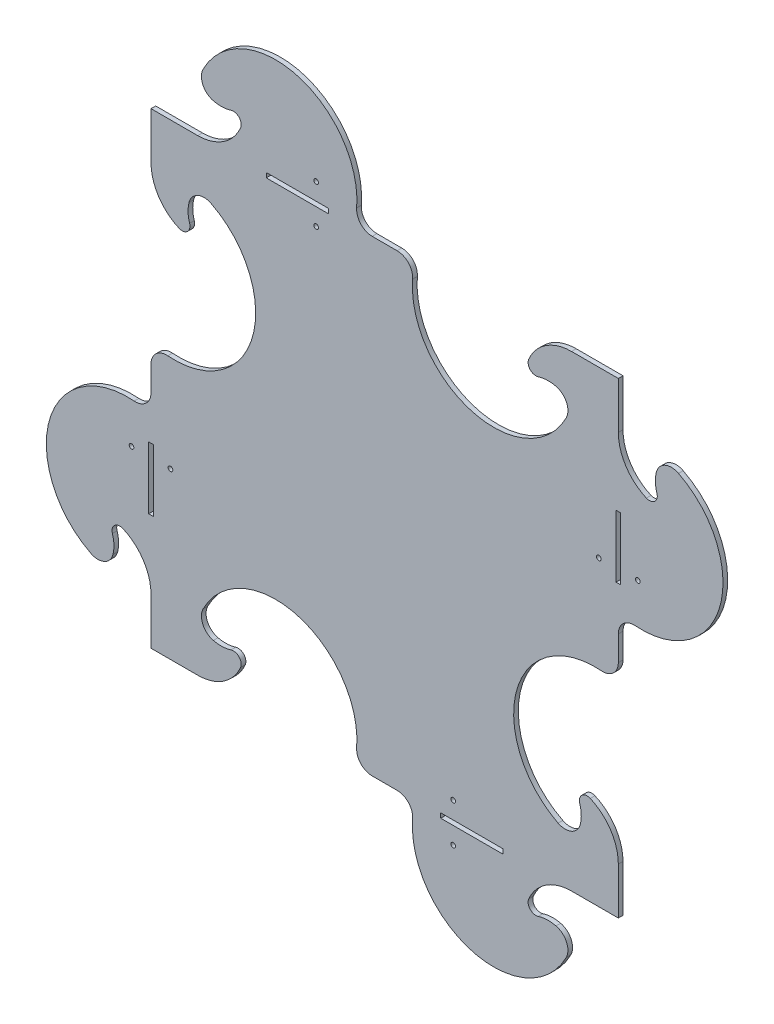
SolidWorks part; units mm, degrees
ref_plane "Plano frontal" through (0, 0, 0) normal (0, 0, 1) x (1, 0, 0)
ref_plane "Plano superior" through (0, 0, 0) normal (0, 1, 0) x (1, 0, 0)
ref_plane "Plano direito" through (0, 0, 0) normal (1, 0, 0) x (0, 0, -1)
sketch "Esboço1" plane through (0, 0, 0) normal (0, 0, 1) x (1, 0, 0)
  line L0 (-241.2037, -59.6514) -> (-241.2037, -29.6514)
  line L1 (-241.2037, 240.3486) -> (58.7963, 240.3486) construction
  line L2 (-241.2037, 240.3486) -> (-241.2037, -59.6514) construction
  line L3 (-241.2037, -59.6514) -> (58.7963, -59.6514) construction
  line L4 (58.7963, 240.3486) -> (58.7963, -59.6514) construction
  line L5 (-241.2037, -29.6514) -> (-241.2037, 0.3486) construction
  line L6 (-241.2037, -29.6514) -> (-241.2037, 70.3486) construction
  line L7 (-241.2037, -29.6514) -> (-271.2037, -29.6514) construction
  line L8 (-241.2037, -29.6514) -> (-241.2037, 0.3486) construction
  line L9 (-241.2037, 240.3486) -> (-241.2037, 210.3486)
  line L10 (-241.2037, 210.3486) -> (-241.2037, 110.3486) construction
  line L11 (-241.2037, 210.3486) -> (-241.2037, 110.3486) construction
  line L12 (-241.2037, 82.3489) -> (-241.2037, 98.3484)
  line L13 (-241.2037, 210.3486) -> (-211.2037, 210.3486) construction
  line L14 (-241.2037, 240.3486) -> (-211.2037, 240.3486)
  line L15 (-211.2037, 240.3486) -> (-111.2037, 240.3486) construction
  line L16 (-211.2037, 240.3486) -> (-211.2037, 270.3486) construction
  line L17 (-211.2037, 240.3486) -> (-181.2037, 240.3486) construction
  line L18 (-99.2034, 240.3486) -> (-83.2039, 240.3486)
  line L19 (58.7963, 240.3486) -> (28.7963, 240.3486)
  line L20 (28.7963, 240.3486) -> (-71.2037, 240.3486) construction
  line L21 (28.7963, 240.3486) -> (-1.2037, 240.3486) construction
  line L22 (28.7963, 240.3486) -> (28.7963, 210.3486) construction
  line L23 (58.7963, 240.3486) -> (58.7963, 210.3486)
  line L24 (-241.2037, -59.6514) -> (-211.2037, -59.6514)
  line L25 (58.7963, -59.6514) -> (28.7963, -59.6514)
  line L26 (58.7963, -59.6514) -> (58.7963, -29.6514)
  line L27 (-211.2037, -59.6514) -> (-181.2037, -59.6514) construction
  line L28 (28.7963, -59.6514) -> (-1.2037, -59.6514) construction
  line L29 (-211.2037, -59.6514) -> (-111.2037, -59.6514) construction
  line L30 (-211.2037, -59.6514) -> (-211.2037, -29.6514) construction
  line L31 (-211.2037, -59.6514) -> (-181.2037, -59.6514) construction
  line L32 (28.7963, -59.6514) -> (-71.2037, -59.6514) construction
  line L33 (28.7963, -59.6514) -> (28.7963, -89.6514) construction
  line L34 (-83.2039, -59.6514) -> (-99.2034, -59.6514)
  line L35 (58.7963, -29.6514) -> (58.7963, 0.3486) construction
  line L36 (58.7963, -29.6514) -> (58.7963, 70.3486) construction
  line L37 (58.7963, -29.6514) -> (58.7963, 70.3486) construction
  line L38 (58.7963, 210.3486) -> (58.7963, 180.3486) construction
  line L39 (58.7963, 210.3486) -> (58.7963, 110.3486) construction
  line L40 (58.7963, 210.3486) -> (88.7963, 210.3486) construction
  line L41 (58.7963, 98.3484) -> (58.7963, 82.3489)
  line L42 (58.7963, -29.6514) -> (28.7963, -29.6514) construction
  line L43 (28.7963, 240.3486) -> (-71.2037, 240.3486) construction
  line L44 (-241.2037, 210.3486) -> (-241.2037, 180.3486) construction
  line L45 (58.7963, 210.3486) -> (58.7963, 180.3486) construction
  arc A0 (-241.2037, -29.6514) -> (-259.2171, -2.15) centre (-271.2037, -29.6514) ccw
  arc A1 (-265.9813, -8.2439) -> (-265.5831, -19.6303) centre (-286.2037, -14.6514) cw
  arc A2 (-279.8296, -26.2004) -> (-252.0075, 72.3813) centre (-256.2037, 20.3486) cw
  arc A3 (-241.2037, 210.3486) -> (-223.1903, 182.8473) centre (-211.2037, 210.3486) ccw
  arc A4 (-216.4261, 188.9412) -> (-216.8243, 200.3276) centre (-196.2037, 195.3486) cw
  arc A5 (-202.5777, 206.8977) -> (-230.3998, 108.316) centre (-226.2037, 160.3486) cw
  arc A6 (-230.3998, 108.316) -> (-241.2037, 98.3484) centre (-231.2037, 98.3484) ccw
  arc A7 (-202.5777, 206.8977) -> (-216.8243, 200.3276) centre (-207.1037, 197.9805) ccw
  arc A8 (-241.2037, 82.3489) -> (-252.0075, 72.3813) centre (-251.2037, 82.3489) cw
  arc A9 (-265.5831, -19.6303) -> (-279.8296, -26.2004) centre (-275.3037, -17.2832) cw
  arc A10 (-223.1903, 182.8473) -> (-216.4261, 188.9412) centre (-221.1925, 187.4309) ccw
  arc A11 (-259.2171, -2.15) -> (-265.9813, -8.2439) centre (-261.2149, -6.7336) ccw
  arc A12 (-211.2037, 240.3486) -> (-183.7024, 258.3621) centre (-211.2037, 270.3486) ccw
  arc A13 (-189.7962, 265.1263) -> (-201.1827, 264.728) centre (-196.2037, 285.3486) cw
  arc A14 (-207.7527, 278.9746) -> (-109.1711, 251.1525) centre (-161.2037, 255.3486) cw
  arc A15 (-99.2034, 240.3486) -> (-109.1711, 251.1525) centre (-99.2034, 250.3486) cw
  arc A16 (-207.7527, 278.9746) -> (-201.1827, 264.728) centre (-198.8356, 274.4487) ccw
  arc A17 (28.7963, 240.3486) -> (1.295, 222.3352) centre (28.7963, 210.3486) ccw
  arc A18 (7.3888, 215.571) -> (18.7753, 215.9693) centre (13.7963, 195.3486) cw
  arc A19 (25.3454, 201.7227) -> (-73.2363, 229.5448) centre (-21.2037, 225.3486) cw
  arc A20 (-189.7962, 265.1263) -> (-183.7024, 258.3621) centre (-188.2859, 260.3598) cw
  arc A21 (18.7753, 215.9693) -> (25.3454, 201.7227) centre (16.4282, 206.2486) cw
  arc A22 (-83.2039, 240.3486) -> (-73.2363, 229.5448) centre (-83.2039, 230.3486) cw
  arc A23 (1.295, 222.3352) -> (7.3888, 215.571) centre (5.8786, 220.3375) ccw
  arc A24 (-211.2037, -59.6514) -> (-183.7024, -41.6379) centre (-211.2037, -29.6514) ccw
  arc A25 (-189.7962, -34.8737) -> (-201.1827, -35.272) centre (-196.2037, -14.6514) cw
  arc A26 (-207.7527, -21.0254) -> (-109.1711, -48.8475) centre (-161.2037, -44.6514) cw
  arc A27 (28.7963, -59.6514) -> (1.295, -77.6648) centre (28.7963, -89.6514) ccw
  arc A28 (7.3888, -84.429) -> (18.7753, -84.0307) centre (13.7963, -104.6514) cw
  arc A29 (25.3454, -98.2773) -> (-73.2363, -70.4552) centre (-21.2037, -74.6514) cw
  arc A30 (-99.2034, -59.6514) -> (-109.1711, -48.8475) centre (-99.2034, -49.6514) cw
  arc A31 (-201.1827, -35.272) -> (-207.7527, -21.0254) centre (-198.8356, -25.5513) cw
  arc A32 (18.7753, -84.0307) -> (25.3454, -98.2773) centre (16.4282, -93.7514) cw
  arc A33 (-83.2039, -59.6514) -> (-73.2363, -70.4552) centre (-83.2039, -69.6514) cw
  arc A34 (-189.7962, -34.8737) -> (-183.7024, -41.6379) centre (-188.2859, -39.6402) cw
  arc A35 (1.295, -77.6648) -> (7.3888, -84.429) centre (5.8786, -79.6625) ccw
  arc A36 (58.7963, -29.6514) -> (40.7829, -2.15) centre (28.7963, -29.6514) ccw
  arc A37 (34.0187, -8.2439) -> (34.4169, -19.6303) centre (13.7963, -14.6514) cw
  arc A38 (20.1704, -26.2004) -> (47.9925, 72.3813) centre (43.7963, 20.3486) cw
  arc A39 (58.7963, 210.3486) -> (76.8097, 182.8473) centre (88.7963, 210.3486) ccw
  arc A40 (83.5739, 188.9412) -> (83.1757, 200.3276) centre (103.7963, 195.3486) cw
  arc A41 (97.4223, 206.8977) -> (69.6002, 108.316) centre (73.7963, 160.3486) cw
  arc A42 (69.6002, 108.316) -> (58.7963, 98.3484) centre (68.7963, 98.3484) ccw
  arc A43 (97.4223, 206.8977) -> (83.1757, 200.3276) centre (92.8963, 197.9805) ccw
  arc A44 (40.7829, -2.15) -> (34.0187, -8.2439) centre (38.7851, -6.7336) ccw
  arc A45 (58.7963, 82.3489) -> (47.9925, 72.3813) centre (48.7963, 82.3489) cw
  arc A46 (34.4169, -19.6303) -> (20.1704, -26.2004) centre (24.6963, -17.2832) cw
  arc A47 (83.5739, 188.9412) -> (76.8097, 182.8473) centre (78.8075, 187.4309) cw
  dimension "D10" = 30
  dimension "D11" = 10
  dimension "D12" = 10
  dimension "D13" = 5
  dimension "D14" = 5
  dimension "D19" = 10
  dimension "D20" = 5
  dimension "D25" = 10
  dimension "D26" = 10
  dimension "D27" = 10
  dimension "D38" = 30
  dimension "D39" = 5
  dimension "D40" = 5
  dimension "D41" = 10
  dimension "D42" = 9.9676
  dimension "D48" = 5
  dimension "D49" = 5
  dimension "D50" = 10
  dimension "D24" = 30
  dimension "D51" = 10
  dimension "D52" = 5
  dimension "D1" = 300
  dimension "D2" = 300
  dimension "D3" = 30
  dimension "D4" = 30
  dimension "D5" = 100
  dimension "D6" = 30
  dimension "D7" = 30
  dimension "D8" = 100
  dimension "D9" = 30
  dimension "D15" = 30
  dimension "D16" = 100
  dimension "D17" = 30
  dimension "D18" = 30
  dimension "D21" = 30
  dimension "D22" = 100
  dimension "D23" = 30
  dimension "D28" = 30
  dimension "D29" = 30
  dimension "D30" = 30
  dimension "D31" = 30
  dimension "D32" = 100
  dimension "D33" = 30
  dimension "D34" = 30
  dimension "D35" = 30
  dimension "D36" = 100
  dimension "D37" = 30
  dimension "D43" = 30
  dimension "D44" = 100
  dimension "D45" = 30
  dimension "D46" = 30
  dimension "D47" = 100
extrude "Ressalto-extrusão1" add sketch "Esboço1" along normal blind 3
sketch "Esboço2" plane through (0, 0, 0) normal (0, 0, -1) x (-1, 0, 0)
  line L0 (211.2037, 240.3486) -> (241.2037, 240.3486) construction
  line L1 (127.2039, 241.8486) -> (167.2039, 241.8486)
  line L2 (127.2039, 241.8486) -> (127.2039, 238.8486)
  line L3 (127.2039, 238.8486) -> (167.2039, 238.8486)
  line L4 (167.2039, 241.8486) -> (167.2039, 238.8486)
  line L5 (-57.2963, 166.3489) -> (-60.2963, 166.3489)
  line L6 (-57.2963, 166.3489) -> (-57.2963, 126.3489)
  line L7 (-57.2963, 126.3489) -> (-60.2963, 126.3489)
  line L8 (-60.2963, 166.3489) -> (-60.2963, 126.3489)
  line L9 (15.2037, -58.1514) -> (55.2037, -58.1514)
  line L10 (15.2037, -58.1514) -> (15.2037, -61.1514)
  line L11 (15.2037, -61.1514) -> (55.2037, -61.1514)
  line L12 (55.2037, -58.1514) -> (55.2037, -61.1514)
  line L13 (239.7037, 54.3484) -> (242.7037, 54.3484)
  line L14 (239.7037, 54.3484) -> (239.7037, 14.3484)
  line L15 (239.7037, 14.3484) -> (242.7037, 14.3484)
  line L16 (242.7037, 54.3484) -> (242.7037, 14.3484)
  line L20 (-58.7963, 82.3489) -> (-58.7963, 98.3484) construction
  line L22 (-28.7963, -59.6514) -> (-58.7963, -59.6514) construction
  line L23 (241.2037, -29.6514) -> (241.2037, -59.6514) construction
  dimension "D1" = 44
  dimension "D2" = 40
  dimension "D3" = 3
  dimension "D4" = 1.5
  dimension "D5" = 40
  dimension "D6" = 3
  dimension "D7" = 1.5
  dimension "D8" = 44
  dimension "D9" = 3
  dimension "D10" = 40
  dimension "D11" = 44
  dimension "D12" = 1.5
  dimension "D13" = 3
  dimension "D14" = 1.5
  dimension "D15" = 40
  dimension "D16" = 44
extrude "Corte-extrusão1" cut sketch "Esboço2" against normal through all
sketch "Esboço3" plane through (0, 0, 3) normal (0, 0, 1) x (1, 0, 0)
  line L0 (-241.2037, 98.3484) -> (-241.2037, 82.3489) construction
  line L1 (-99.2034, -59.6514) -> (-83.2039, -59.6514) construction
  line L2 (-83.2039, 240.3486) -> (-99.2034, 240.3486) construction
  line L3 (-241.2037, -29.6514) -> (-241.2037, -59.6514) construction
  line L4 (58.7963, 82.3489) -> (58.7963, 98.3484) construction
  circle A0 centre (-228.7037, 46.3486) radius 1.5
  circle A1 centre (-47.2037, -47.1514) radius 1.5
  circle A2 centre (46.2963, 134.3486) radius 1.5
  circle A3 centre (-135.2037, 227.8486) radius 1.5
  circle A4 centre (-47.2037, -72.1514) radius 1.5
  circle A5 centre (-253.7037, 46.3486) radius 1.5
  circle A6 centre (-135.2037, 252.8486) radius 1.5
  circle A7 centre (71.2963, 134.3486) radius 1.5
  dimension "D1" = 3
  dimension "D2" = 106
  dimension "D3" = 3
  dimension "D4" = 3
  dimension "D5" = 12.5
  dimension "D6" = 12.5
  dimension "D7" = 12.5
  dimension "D8" = 106
  dimension "D9" = 12.5
  dimension "D10" = 3
  dimension "D11" = 106
  dimension "D12" = 106
  dimension "D13" = 12.5
  dimension "D14" = 3
  dimension "D15" = 106
  dimension "D16" = 3
  dimension "D17" = 106
  dimension "D18" = 12.5
  dimension "D19" = 106
  dimension "D20" = 3
  dimension "D21" = 12.5
  dimension "D22" = 3
  dimension "D23" = 106
  dimension "D24" = 12.5
extrude "Corte-extrusão2" cut sketch "Esboço3" against normal through all
